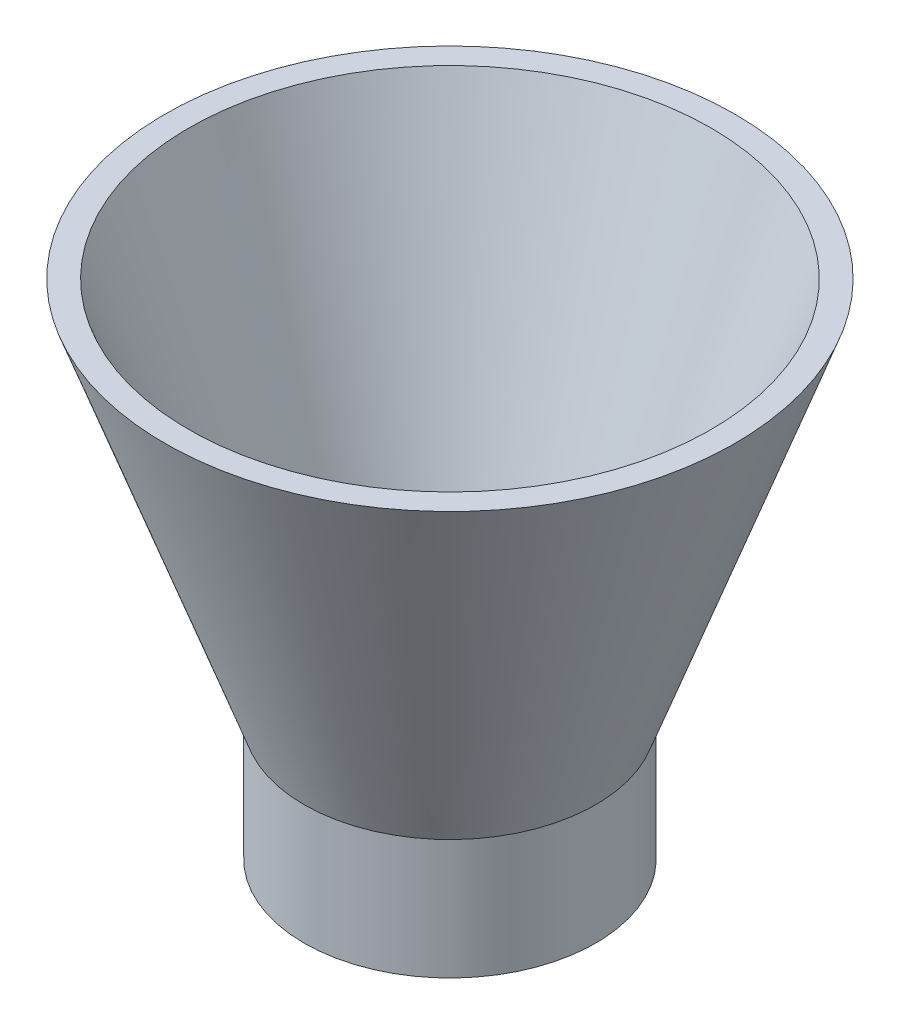
SolidWorks part; units mm, degrees
ref_plane "Front Plane" through (0, 0, 0) normal (0, 0, 1) x (1, 0, 0)
ref_plane "Top Plane" through (0, 0, 0) normal (0, 1, 0) x (1, 0, 0)
ref_plane "Right Plane" through (0, 0, 0) normal (1, 0, 0) x (0, 0, -1)
sketch "Sketch1" plane through (0, 0, 0) normal (0, 0, 1) x (1, 0, 0)
  line L0 (0, 0) -> (0, 50000) construction
  line L1 (34.6822, 50.8) -> (16.1925, 0)
  line L2 (16.1925, 0) -> (19.3675, 0)
  line L3 (19.3675, 0) -> (37.8572, 50.8)
  line L4 (37.8572, 50.8) -> (34.6822, 50.8)
  line L5 (0, 0) -> (50000, 0) construction
  line L6 (16.1925, 0) -> (16.1925, -12.7)
  line L7 (16.1925, -12.7) -> (19.3675, -12.7)
  line L8 (19.3675, -12.7) -> (19.3675, 0)
  line L9 (19.3675, -12.7) -> (19.3675, -15.9206)
  line L10 (19.3675, -15.9206) -> (0, -15.9206)
  line L11 (0, -15.9206) -> (0, -12.7)
  line L12 (0, -12.7) -> (16.1925, -12.7)
  point P9 (36.2697, 50.8)
  dimension "D1" = 70
  dimension "D2" = 3.175
  dimension "D3" = 50.8
  dimension "D4" = 16.1925
  dimension "D5" = 12.7
  dimension "D6" = 15.9206
revolve "Revolve1" add sketch "Sketch1" angle 360 about L0
